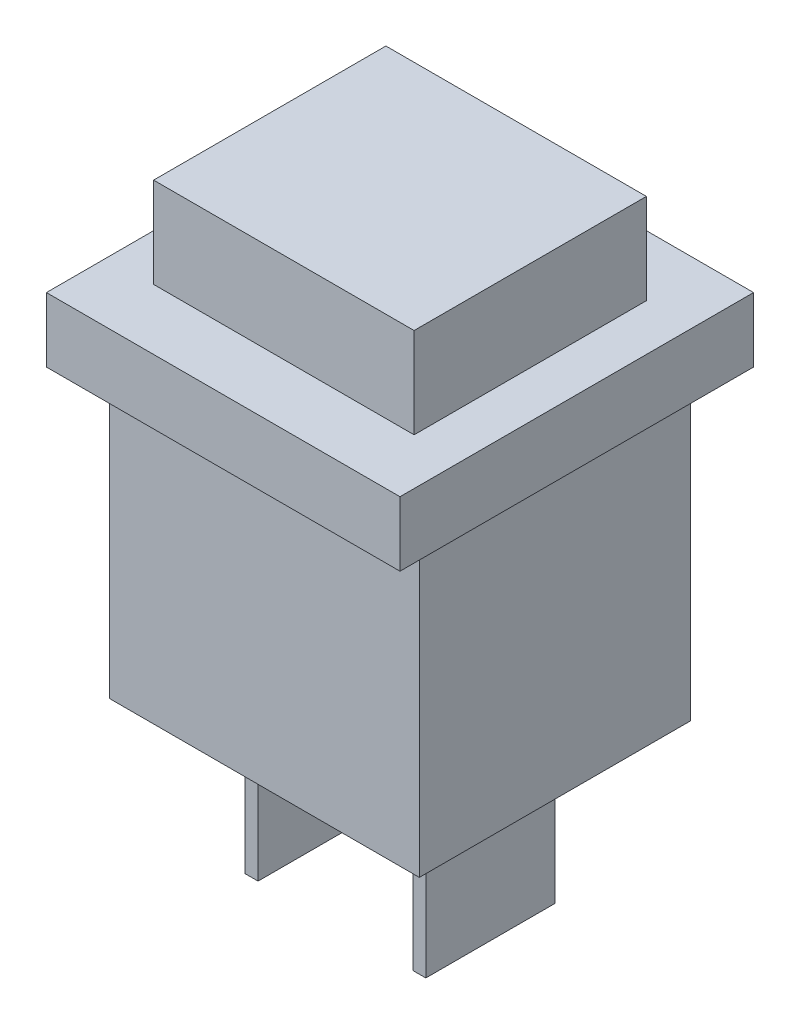
SolidWorks part; units mm, degrees
ref_plane "Спереди" through (0, 0, 0) normal (0, 0, 1) x (1, 0, 0)
ref_plane "Сверху" through (0, 0, 0) normal (0, 1, 0) x (1, 0, 0)
ref_plane "Справа" through (0, 0, 0) normal (1, 0, 0) x (0, 0, -1)
sketch "Эскиз1" plane through (0, 0, 0) normal (0, 1, 0) x (1, 0, 0)
  line L1 (0, 0) -> (12, 0)
  line L2 (0, 0) -> (0, 10.5)
  line L3 (0, 10.5) -> (12, 10.5)
  line L4 (12, 0) -> (12, 10.5)
extrude "Бобышка-Вытянуть1" add sketch "Эскиз1" along normal blind 11.5
sketch "Эскиз2" plane through (0, 11.5, 0) normal (0, 1, 0) x (1, 0, 0)
  line L1 (12.85, -1.6) -> (-0.85, -1.6)
  line L2 (12.85, -1.6) -> (12.85, 12.1)
  line L3 (12.85, 12.1) -> (-0.85, 12.1)
  line L4 (-0.85, -1.6) -> (-0.85, 12.1)
  line L5 (0, 0) -> (12, 0) construction
  dimension "D1" = 13.7
  dimension "D2" = 13.7
  dimension "D3" = 0.85
  dimension "D4" = 1.6
extrude "Бобышка-Вытянуть2" add sketch "Эскиз2" along normal blind 2.5
sketch "Эскиз3" plane through (0, 14, 0) normal (0, 1, 0) x (1, 0, 0)
  line L0 (6, 12.1) -> (6, -1.6) construction
  line L1 (0.9534, 9.75) -> (11.0466, 9.75)
  line L2 (0.9534, 9.75) -> (0.9534, 0.75)
  line L3 (0.9534, 0.75) -> (11.0466, 0.75)
  line L4 (11.0466, 9.75) -> (11.0466, 0.75)
  line L5 (12.85, 12.1) -> (-0.85, 12.1) construction
  line L6 (-0.85, -1.6) -> (12.85, -1.6) construction
  line L7 (-0.85, 12.1) -> (-0.85, -1.6) construction
  line L8 (-0.85, 5.25) -> (12.85, 5.25) construction
  line L9 (12.85, -1.6) -> (12.85, 12.1) construction
  line L10 (6, 9.75) -> (6, 0.75) construction
  line L11 (0.9534, 5.25) -> (11.0466, 5.25) construction
extrude "Бобышка-Вытянуть3" add sketch "Эскиз3" along normal blind 3.5 separate body
sketch "Эскиз4" plane through (0, 0, 0) normal (0, -1, 0) x (-1, 0, 0)
  line L0 (-2.5, 2.75) -> (-3, 2.75)
  line L1 (-9, 2.75) -> (-9.5, 2.75)
  line L2 (-9, 2.75) -> (-9, 7.75)
  line L3 (-9, 7.75) -> (-9.5, 7.75)
  line L4 (-9.5, 2.75) -> (-9.5, 7.75)
  line L5 (-2.5, 2.75) -> (-2.5, 7.75)
  line L6 (-2.5, 7.75) -> (-3, 7.75)
  line L7 (-3, 2.75) -> (-3, 7.75)
  line L11 (0, 5.25) -> (-12, 5.25) construction
  line L12 (0, 10.5) -> (0, 0) construction
  line L13 (-12, 0) -> (-12, 10.5) construction
  line L14 (-2.5, 5.25) -> (-3, 5.25) construction
  dimension "D1" = 6
  dimension "D2" = 0.5
  dimension "D3" = 0.5
  dimension "D4" = 5
  dimension "D5" = 5
  dimension "D6" = 2.5
extrude "Бобышка-Вытянуть4" add sketch "Эскиз4" along normal blind 6
